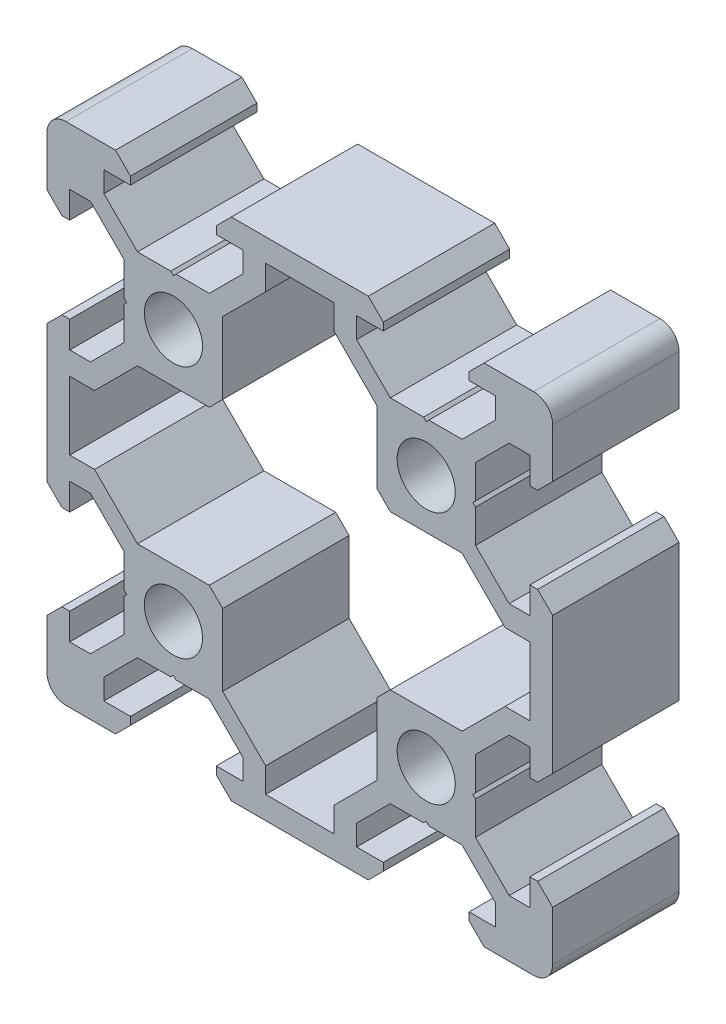
SolidWorks part; units mm, degrees
ref_plane "Front Plane" through (0, 0, 0) normal (0, 0, 1) x (1, 0, 0)
ref_plane "Top Plane" through (0, 0, 0) normal (0, 1, 0) x (1, 0, 0)
ref_plane "Right Plane" through (0, 0, 0) normal (1, 0, 0) x (0, 0, -1)
sketch "Sketch1" plane through (0, 0, 0) normal (0, 0, 1) x (1, 0, 0)
  line L0 (-12.4674, 6.4719) -> (-6.7887, 6.4719)
  line L1 (-15.8674, 3.0719) -> (-12.4674, 6.4719)
  line L2 (-17.8281, 3.0719) -> (-15.8674, 3.0719)
  line L3 (-17.8281, -2.3281) -> (-17.8281, 3.0719)
  line L4 (-17.8281, -2.3281) -> (-15.8674, -2.3281)
  line L5 (-15.8674, -2.3281) -> (-12.4674, -5.7281)
  line L6 (-12.4674, -5.7281) -> (-6.7887, -5.7281)
  line L7 (-5.7281, -6.7887) -> (-6.7887, -5.7281)
  line L8 (-5.7281, -12.4674) -> (-5.7281, -6.7887)
  line L9 (-2.3281, -15.8674) -> (-5.7281, -12.4674)
  line L10 (-2.3281, -17.8281) -> (-2.3281, -15.8674)
  line L11 (3.0719, -17.8281) -> (-2.3281, -17.8281)
  line L12 (3.0719, -17.8281) -> (3.0719, -15.8674)
  line L13 (3.0719, -15.8674) -> (6.4719, -12.4674)
  line L14 (6.4719, -12.4674) -> (6.4719, -6.7887)
  line L15 (7.5326, -5.7281) -> (6.4719, -6.7887)
  line L16 (13.2113, -5.7281) -> (7.5326, -5.7281)
  line L17 (16.6113, -2.3281) -> (13.2113, -5.7281)
  line L18 (18.5719, -2.3281) -> (16.6113, -2.3281)
  line L19 (18.5719, -2.3281) -> (18.5719, 3.0719)
  line L20 (18.5719, 3.0719) -> (16.6113, 3.0719)
  line L21 (16.6113, 3.0719) -> (13.2113, 6.4719)
  line L22 (13.2113, 6.4719) -> (7.5326, 6.4719)
  line L23 (6.4719, 13.2113) -> (6.4719, 7.5326)
  line L24 (6.4719, 7.5326) -> (7.5326, 6.4719)
  line L25 (3.0719, 16.6113) -> (6.4719, 13.2113)
  line L26 (3.0719, 18.5719) -> (3.0719, 16.6113)
  line L27 (3.0719, 18.5719) -> (-2.3281, 18.5719)
  line L28 (-2.3281, 18.5719) -> (-2.3281, 16.6113)
  line L29 (-2.3281, 16.6113) -> (-5.7281, 13.2113)
  line L30 (-5.7281, 13.2113) -> (-5.7281, 7.5326)
  line L31 (-6.7887, 6.4719) -> (-5.7281, 7.5326)
  line L32 (14.2719, -9.8381) -> (14.0619, -9.6281)
  line L33 (14.0619, -9.6281) -> (14.2719, -9.4181)
  line L34 (14.2719, -9.4181) -> (14.2719, -6.7887)
  line L35 (14.2719, -6.7887) -> (16.9326, -4.1281)
  line L36 (16.9326, -4.1281) -> (18.5719, -4.1281)
  line L37 (18.5719, -4.1281) -> (18.5719, -6.2331)
  line L38 (18.5719, -6.2331) -> (19.1869, -6.2331)
  line L39 (19.1869, -6.2331) -> (20.3719, -5.0481)
  line L40 (20.3719, -5.0481) -> (20.3719, 5.7919)
  line L41 (20.3719, 5.7919) -> (19.1869, 6.9769)
  line L42 (19.1869, 6.9769) -> (18.5719, 6.9769)
  line L43 (18.5719, 6.9769) -> (18.5719, 4.8719)
  line L44 (18.5719, 4.8719) -> (16.9326, 4.8719)
  line L45 (16.9326, 4.8719) -> (14.2719, 7.5326)
  line L46 (14.2719, 7.5326) -> (14.2719, 10.1619)
  line L47 (14.2719, 10.1619) -> (14.0619, 10.3719)
  line L48 (14.0619, 10.3719) -> (14.2719, 10.5819)
  line L49 (14.2719, 10.5819) -> (14.2719, 13.2113)
  line L50 (14.2719, 13.2113) -> (16.9326, 15.8719)
  line L51 (16.9326, 15.8719) -> (18.5719, 15.8719)
  line L52 (18.5719, 15.8719) -> (18.5719, 13.7669)
  line L53 (18.5719, 13.7669) -> (19.1869, 13.7669)
  line L54 (19.1869, 13.7669) -> (20.3719, 14.9519)
  line L55 (20.3719, 14.9519) -> (20.3719, 18.8719)
  line L56 (18.8719, 20.3719) -> (14.9519, 20.3719)
  line L57 (14.9519, 20.3719) -> (13.7669, 19.1869)
  line L58 (13.7669, 19.1869) -> (13.7669, 18.5719)
  line L59 (13.7669, 18.5719) -> (15.8719, 18.5719)
  line L60 (15.8719, 18.5719) -> (15.8719, 16.9326)
  line L61 (15.8719, 16.9326) -> (13.2113, 14.2719)
  line L62 (13.2113, 14.2719) -> (10.5819, 14.2719)
  line L63 (10.5819, 14.2719) -> (10.3719, 14.0619)
  line L64 (10.3719, 14.0619) -> (10.1619, 14.2719)
  line L65 (10.1619, 14.2719) -> (7.5326, 14.2719)
  line L66 (7.5326, 14.2719) -> (4.8719, 16.9326)
  line L67 (4.8719, 16.9326) -> (4.8719, 18.5719)
  line L68 (4.8719, 18.5719) -> (6.9769, 18.5719)
  line L69 (6.9769, 18.5719) -> (6.9769, 19.1869)
  line L70 (6.9769, 19.1869) -> (5.7919, 20.3719)
  line L71 (5.7919, 20.3719) -> (-5.0481, 20.3719)
  line L72 (-5.0481, 20.3719) -> (-6.2331, 19.1869)
  line L73 (-6.2331, 19.1869) -> (-6.2331, 18.5719)
  line L74 (-6.2331, 18.5719) -> (-4.1281, 18.5719)
  line L75 (-4.1281, 18.5719) -> (-4.1281, 16.9326)
  line L76 (-4.1281, 16.9326) -> (-6.7887, 14.2719)
  line L77 (-6.7887, 14.2719) -> (-9.4181, 14.2719)
  line L78 (-9.4181, 14.2719) -> (-9.6281, 14.0619)
  line L79 (-9.6281, 14.0619) -> (-9.8381, 14.2719)
  line L80 (-9.8381, 14.2719) -> (-12.4674, 14.2719)
  line L81 (-12.4674, 14.2719) -> (-15.1281, 16.9326)
  line L82 (-15.1281, 16.9326) -> (-15.1281, 18.5719)
  line L83 (-15.1281, 18.5719) -> (-13.0231, 18.5719)
  line L84 (-13.0231, 18.5719) -> (-13.0231, 19.1869)
  line L85 (-13.0231, 19.1869) -> (-14.2081, 20.3719)
  line L86 (-14.2081, 20.3719) -> (-18.1281, 20.3719)
  line L87 (-19.6281, 18.8719) -> (-19.6281, 14.9519)
  line L88 (-19.6281, 14.9519) -> (-18.4431, 13.7669)
  line L89 (-18.4431, 13.7669) -> (-17.8281, 13.7669)
  line L90 (-17.8281, 13.7669) -> (-17.8281, 15.8719)
  line L91 (-17.8281, 15.8719) -> (-16.1887, 15.8719)
  line L92 (-16.1887, 15.8719) -> (-13.5281, 13.2113)
  line L93 (-13.5281, 13.2113) -> (-13.5281, 10.5819)
  line L94 (-13.5281, 10.5819) -> (-13.3181, 10.3719)
  line L95 (-13.3181, 10.3719) -> (-13.5281, 10.1619)
  line L96 (-13.5281, 10.1619) -> (-13.5281, 7.5326)
  line L97 (-13.5281, 7.5326) -> (-16.1887, 4.8719)
  line L98 (-16.1887, 4.8719) -> (-17.8281, 4.8719)
  line L99 (-17.8281, 4.8719) -> (-17.8281, 6.9769)
  line L100 (-17.8281, 6.9769) -> (-18.4431, 6.9769)
  line L101 (-18.4431, 6.9769) -> (-19.6281, 5.7919)
  line L102 (-19.6281, 5.7919) -> (-19.6281, -5.0481)
  line L103 (-19.6281, -5.0481) -> (-18.4431, -6.2331)
  line L104 (-18.4431, -6.2331) -> (-17.8281, -6.2331)
  line L105 (-17.8281, -6.2331) -> (-17.8281, -4.1281)
  line L106 (-17.8281, -4.1281) -> (-16.1887, -4.1281)
  line L107 (-16.1887, -4.1281) -> (-13.5281, -6.7887)
  line L108 (-13.5281, -6.7887) -> (-13.5281, -9.4181)
  line L109 (-13.5281, -9.4181) -> (-13.3181, -9.6281)
  line L110 (-13.3181, -9.6281) -> (-13.5281, -9.8381)
  line L111 (-13.5281, -9.8381) -> (-13.5281, -12.4674)
  line L112 (-13.5281, -12.4674) -> (-16.1887, -15.1281)
  line L113 (-16.1887, -15.1281) -> (-17.8281, -15.1281)
  line L114 (-17.8281, -15.1281) -> (-17.8281, -13.0231)
  line L115 (-17.8281, -13.0231) -> (-18.4431, -13.0231)
  line L116 (-18.4431, -13.0231) -> (-19.6281, -14.2081)
  line L117 (-19.6281, -14.2081) -> (-19.6281, -18.1281)
  line L118 (-18.1281, -19.6281) -> (-14.2081, -19.6281)
  line L119 (-14.2081, -19.6281) -> (-13.0231, -18.4431)
  line L120 (-13.0231, -18.4431) -> (-13.0231, -17.8281)
  line L121 (-13.0231, -17.8281) -> (-15.1281, -17.8281)
  line L122 (-15.1281, -17.8281) -> (-15.1281, -16.1887)
  line L123 (-15.1281, -16.1887) -> (-12.4674, -13.5281)
  line L124 (-12.4674, -13.5281) -> (-9.8381, -13.5281)
  line L125 (-9.8381, -13.5281) -> (-9.6281, -13.3181)
  line L126 (-9.6281, -13.3181) -> (-9.4181, -13.5281)
  line L127 (-9.4181, -13.5281) -> (-6.7887, -13.5281)
  line L128 (-6.7887, -13.5281) -> (-4.1281, -16.1887)
  line L129 (-4.1281, -16.1887) -> (-4.1281, -17.8281)
  line L130 (-4.1281, -17.8281) -> (-6.2331, -17.8281)
  line L131 (-6.2331, -17.8281) -> (-6.2331, -18.4431)
  line L132 (-6.2331, -18.4431) -> (-5.0481, -19.6281)
  line L133 (-5.0481, -19.6281) -> (5.7919, -19.6281)
  line L134 (5.7919, -19.6281) -> (6.9769, -18.4431)
  line L135 (6.9769, -18.4431) -> (6.9769, -17.8281)
  line L136 (6.9769, -17.8281) -> (4.8719, -17.8281)
  line L137 (4.8719, -17.8281) -> (4.8719, -16.1887)
  line L138 (4.8719, -16.1887) -> (7.5326, -13.5281)
  line L139 (7.5326, -13.5281) -> (10.1619, -13.5281)
  line L140 (10.1619, -13.5281) -> (10.3719, -13.3181)
  line L141 (10.3719, -13.3181) -> (10.5819, -13.5281)
  line L142 (10.5819, -13.5281) -> (13.2113, -13.5281)
  line L143 (13.2113, -13.5281) -> (15.8719, -16.1887)
  line L144 (15.8719, -16.1887) -> (15.8719, -17.8281)
  line L145 (15.8719, -17.8281) -> (13.7669, -17.8281)
  line L146 (13.7669, -17.8281) -> (13.7669, -18.4431)
  line L147 (13.7669, -18.4431) -> (14.9519, -19.6281)
  line L148 (14.9519, -19.6281) -> (18.8719, -19.6281)
  line L149 (20.3719, -18.1281) -> (20.3719, -14.2081)
  line L150 (20.3719, -14.2081) -> (19.1869, -13.0231)
  line L151 (19.1869, -13.0231) -> (18.5719, -13.0231)
  line L152 (18.5719, -13.0231) -> (18.5719, -15.1281)
  line L153 (18.5719, -15.1281) -> (16.9326, -15.1281)
  line L154 (16.9326, -15.1281) -> (14.2719, -12.4674)
  line L155 (14.2719, -12.4674) -> (14.2719, -9.8381)
  arc A0 (20.3719, 18.8719) -> (18.8719, 20.3719) centre (18.8719, 18.8719) ccw
  arc A1 (-18.1281, 20.3719) -> (-19.6281, 18.8719) centre (-18.1281, 18.8719) ccw
  arc A2 (-19.6281, -18.1281) -> (-18.1281, -19.6281) centre (-18.1281, -18.1281) ccw
  arc A3 (18.8719, -19.6281) -> (20.3719, -18.1281) centre (18.8719, -18.1281) ccw
  circle A4 centre (-9.6281, -9.6281) radius 2.3
  circle A5 centre (10.3719, -9.6281) radius 2.3
  circle A6 centre (10.3719, 10.3719) radius 2.3
  circle A7 centre (-9.6281, 10.3719) radius 2.3
extrude "Boss-Extrude1" add sketch "Sketch1" along normal blind 10
